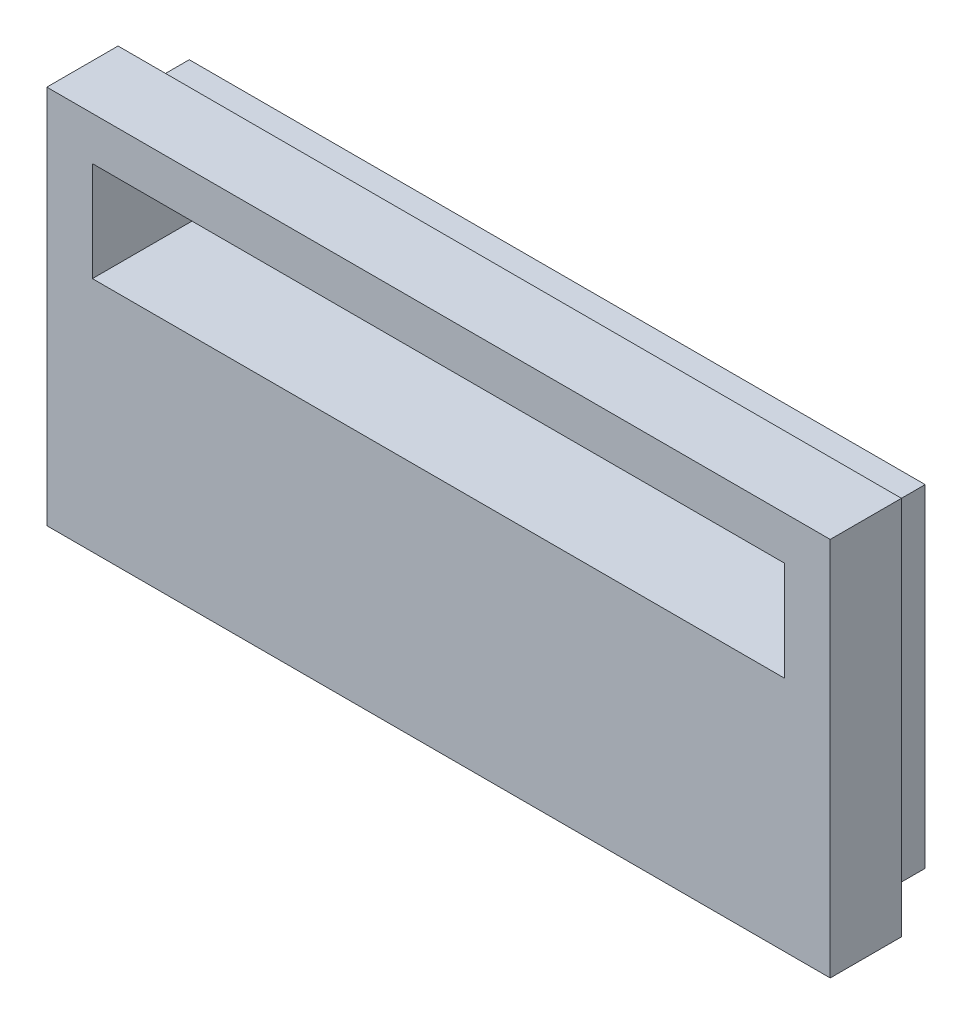
SolidWorks part; units mm, degrees
ref_plane "Front Plane" through (0, 0, 0) normal (0, 0, 1) x (1, 0, 0)
ref_plane "Top Plane" through (0, 0, 0) normal (0, 1, 0) x (1, 0, 0)
ref_plane "Right Plane" through (0, 0, 0) normal (1, 0, 0) x (0, 0, -1)
sketch "Sketch1" plane through (0, 0, 0) normal (0, 0, 1) x (1, 0, 0)
  line L1 (-8.25, -4) -> (8.25, -4)
  line L2 (-8.25, -4) -> (-8.25, 4)
  line L3 (-8.25, 4) -> (8.25, 4)
  line L4 (8.25, -4) -> (8.25, 4)
  line L5 (-8.25, -4) -> (8.25, 4) construction
  line L6 (-8.25, 4) -> (8.25, -4) construction
  point P0 (0, 0)
  dimension "D1" = 16.5
  dimension "D2" = 8
extrude "Boss-Extrude1" add sketch "Sketch1" along normal blind 1.5
sketch "Sketch2" plane through (0, 0, 0) normal (0, 0, -1) x (-1, 0, 0)
  line L1 (-7.75, -3.5) -> (7.75, -3.5)
  line L2 (-7.75, -3.5) -> (-7.75, 3.5)
  line L3 (-7.75, 3.5) -> (7.75, 3.5)
  line L4 (7.75, -3.5) -> (7.75, 3.5)
  line L5 (-7.75, -3.5) -> (7.75, 3.5) construction
  line L6 (-7.75, 3.5) -> (7.75, -3.5) construction
  point P0 (0, 0)
  dimension "D1" = 15.5
  dimension "D2" = 7
extrude "Boss-Extrude2" add sketch "Sketch2" along normal blind 1
sketch "Sketch3" plane through (0, 0, -1) normal (0, 0, -1) x (-1, 0, 0)
  line L1 (-7.2901, 3.085) -> (7.2901, 3.085)
  line L2 (-7.2901, 3.085) -> (-7.2901, 0.9868)
  line L3 (-7.2901, 0.9868) -> (7.2901, 0.9868)
  line L4 (7.2901, 3.085) -> (7.2901, 0.9868)
  line L5 (-7.2901, 3.085) -> (7.2901, 0.9868) construction
  line L6 (-7.2901, 0.9868) -> (7.2901, 3.085) construction
  point P0 (0, 2.0359)
extrude "Cut-Extrude2" cut sketch "Sketch3" against normal blind 5
